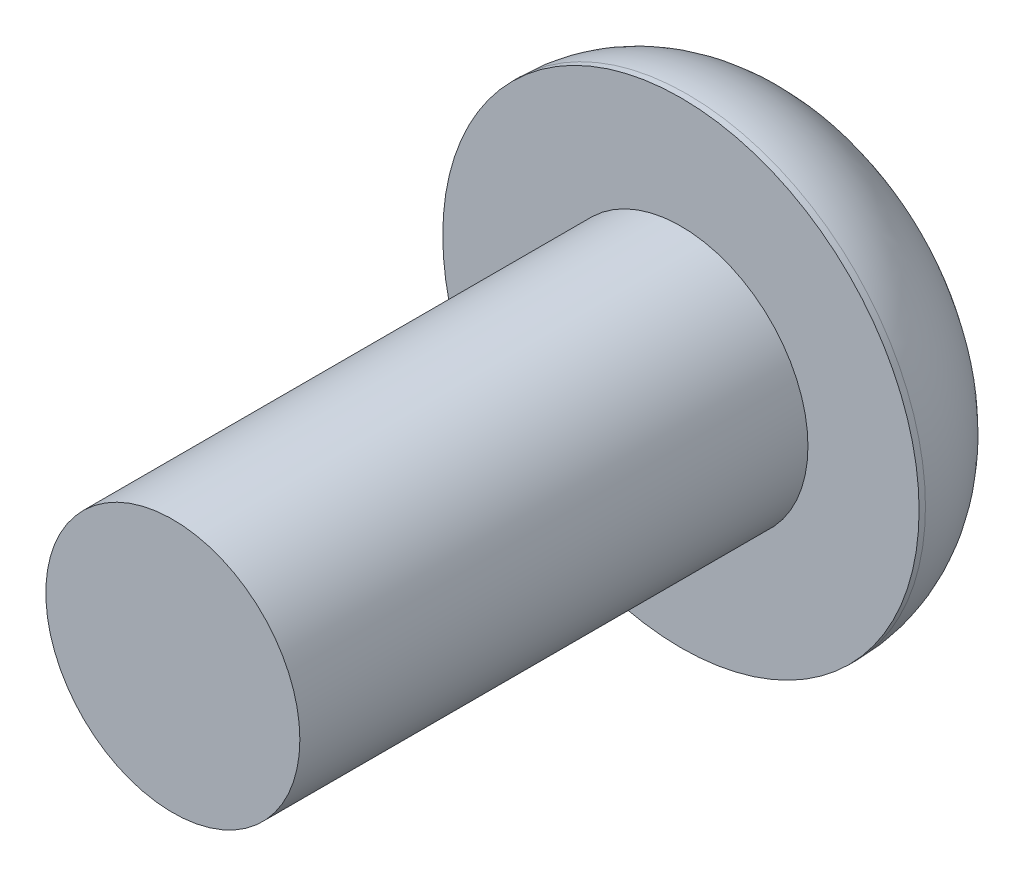
SolidWorks part; units mm, degrees
ref_plane "前视基准面" through (0, 0, 0) normal (0, 0, 1) x (1, 0, 0)
ref_plane "上视基准面" through (0, 0, 0) normal (0, 1, 0) x (1, 0, 0)
ref_plane "右视基准面" through (0, 0, 0) normal (1, 0, 0) x (0, 0, -1)
sketch "草图1" plane through (0, 0, 0) normal (0, 0, 1) x (1, 0, 0)
  circle A0 centre (0, 0) radius 2
extrude "凸台-拉伸1" add sketch "草图1" along normal blind 8
sketch "草图2" plane through (0, 0, 0) normal (0, 0, -1) x (-1, 0, 0)
  circle A0 centre (0, 0) radius 3.75
extrude "凸台-拉伸2" add sketch "草图2" along normal blind 2.1
fillet "圆角1" radius 2 1 edges at (-3.75, 0, -2.1)
